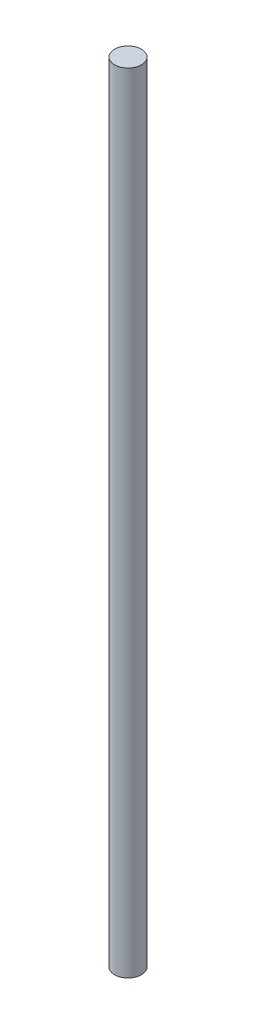
SolidWorks part; units mm, degrees
ref_plane "Front Plane" through (0, 0, 0) normal (0, 0, 1) x (1, 0, 0)
ref_plane "Top Plane" through (0, 0, 0) normal (0, 1, 0) x (1, 0, 0)
ref_plane "Right Plane" through (0, 0, 0) normal (1, 0, 0) x (0, 0, -1)
sketch "Sketch1" plane through (0, 0, 0) normal (0, 1, 0) x (1, 0, 0)
  circle A0 centre (0, 0) radius 0.65
  dimension "D1" = 1.3
extrude "Boss-Extrude1" add sketch "Sketch1" along normal blind 38
